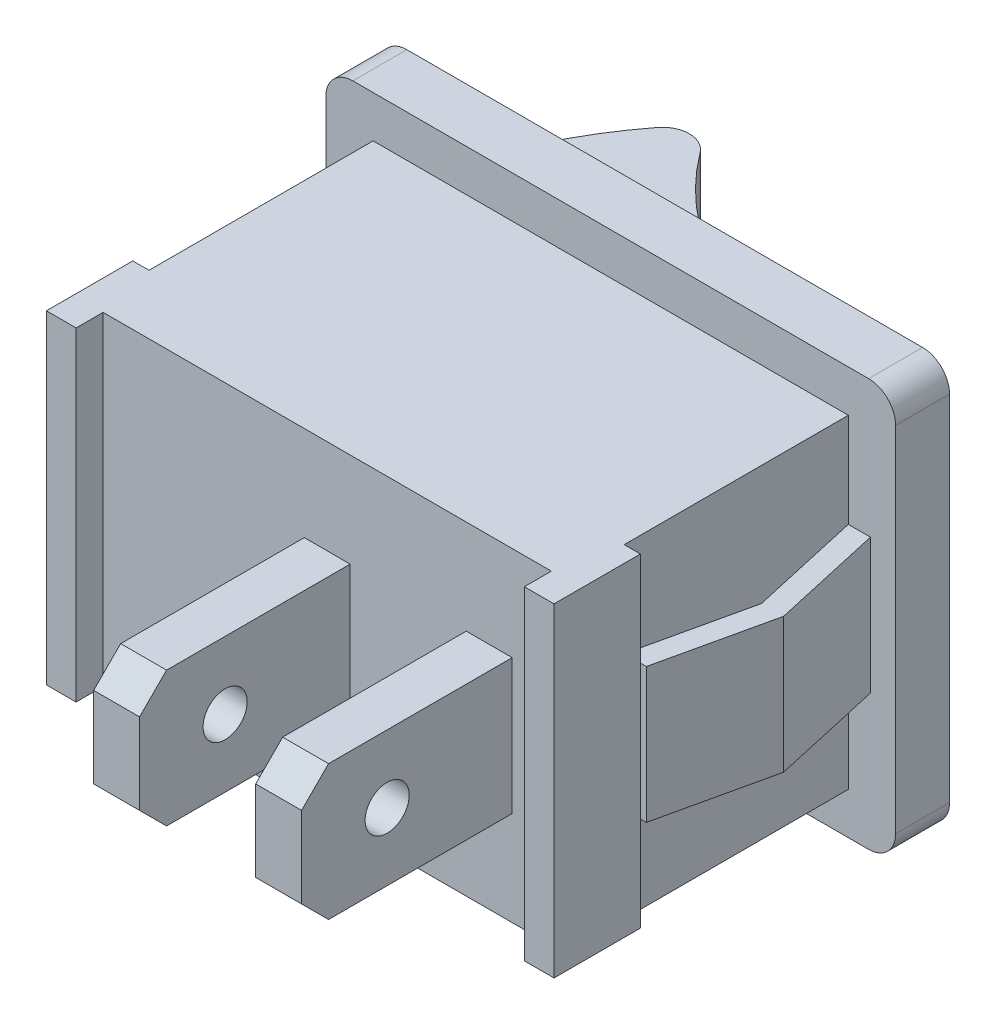
SolidWorks part; units mm, degrees
ref_plane "Front Plane" through (0, 0, 0) normal (0, 0, 1) x (1, 0, 0)
ref_plane "Top Plane" through (0, 0, 0) normal (0, 1, 0) x (1, 0, 0)
ref_plane "Right Plane" through (0, 0, 0) normal (1, 0, 0) x (0, 0, -1)
sketch "Sketch1" plane through (0, 0, 0) normal (0, 1, 0) x (1, 0, 0)
  line L0 (-55, 0) -> (55, 0) construction
  line L1 (-8.3, 0) -> (8.3, 0)
  line L2 (-8.8, 2.2) -> (-8.8, 10.5)
  line L3 (-8.8, 10.5) -> (8.8, 10.5)
  line L4 (8.8, 2.2) -> (8.8, 10.5)
  line L6 (0, -55) -> (0, 55) construction
  line L7 (8.3, -1) -> (8.3, 0)
  line L8 (8.8, 2.2) -> (9.4, 2.2)
  line L9 (-9.4, 2.2) -> (-9.4, -1)
  line L10 (8.3, -1) -> (9.4, -1)
  line L11 (9.4, 2.2) -> (9.4, -1)
  line L12 (-8.3, -1) -> (-9.4, -1)
  line L13 (-8.3, -1) -> (-8.3, 0)
  line L14 (-8.8, 2.2) -> (-9.4, 2.2)
  dimension "D1" = 17.6
  dimension "D2" = 8.3
  dimension "D3" = 9.4
  dimension "D4" = 8.3
  dimension "D5" = 10.5
  dimension "D6" = 1
extrude "Boss-Extrude1" add sketch "Sketch1" along normal mid plane 12
sketch "Sketch2" plane through (0, 0, -10.5) normal (0, 0, -1) x (-1, 0, 0)
  line L0 (8.8, 6) -> (8.8, -6) construction
  line L1 (-10.55, 7.55) -> (10.55, 7.55)
  line L2 (-10.55, 7.55) -> (-10.55, -7.55)
  line L3 (-10.55, -7.55) -> (10.55, -7.55)
  line L4 (10.55, 7.55) -> (10.55, -7.55)
  line L5 (8.8, 6) -> (8.8, -6) construction
  line L6 (8.8, 0) -> (-10.55, 0) construction
  line L7 (0, 0) -> (0, 7.55) construction
  line L8 (0, 55) -> (0, -55) construction
  dimension "D1" = 21.1
  dimension "D2" = 15.1
extrude "Boss-Extrude2" add sketch "Sketch2" along normal blind 2
fillet "Fillet1" radius 1 4 edges at (-10.55, 7.55, -11.5) (-10.55, -7.55, -11.5) (10.55, -7.55, -11.5) (10.55, 7.55, -11.5)
sketch "Sketch3" plane through (0, 0, 0) normal (1, 0, 0) x (0, 0, -1)
  line L0 (0, 8.305) -> (0, -8.305) construction
  line L1 (0, 2.5) -> (-6.8, 2.5)
  line L2 (0, 2.5) -> (0, -2.5)
  line L3 (0, -2.5) -> (-6.8, -2.5)
  line L4 (-7.8, 1.5) -> (-7.8, -1.5)
  line L5 (10.5, 0) -> (0, 0) construction
  line L6 (10.5, 6) -> (10.5, -6) construction
  line L7 (-6.8, 2.5) -> (-7.8, 1.5)
  line L8 (-6.8, -2.5) -> (-7.8, -1.5)
  line L9 (7.425, 0) -> (-7.425, 0) construction
  circle A0 centre (-4.631, 0) radius 0.817
  point P1 (-7.8, -2.5)
  point P3 (-7.8, 2.5)
  dimension "D1" = 5
  dimension "D2" = 7.8
extrude "Boss-Extrude3" add sketch "Sketch3" along normal mid plane 1.7
pattern_linear "LPattern1" count 2 spacing 6 along (1, 0, 0) of "Boss-Extrude3"
sketch "Sketch4" plane through (0, 0, 0) normal (0, 1, 0) x (1, 0, 0)
  line L0 (7.177, 12.8006) -> (7.177, 12.5)
  line L1 (-9.55, 12.5) -> (9.55, 12.5) construction
  line L2 (-7.7109, 12.5) -> (7.177, 12.5)
  arc A0 (-3.622, 17.4321) -> (7.177, 12.8006) centre (5.7794, 24.4473) ccw
  arc A1 (-5.214, 17.4466) -> (-7.7109, 12.5) centre (6.2774, 8.5425) ccw
  arc A2 (-3.622, 17.4321) -> (-5.214, 17.4466) centre (-4.4235, 16.8341) ccw
  dimension "D1" = 1
extrude "Boss-Extrude4" add sketch "Sketch4" along normal mid plane 9.5
sketch "Sketch5" plane through (0, 0, 0) normal (0, 1, 0) x (1, 0, 0)
  line L0 (8.8, 10.5) -> (9.7302, 6.35)
  line L1 (9.7302, 6.35) -> (8.8, 2.2)
  line L2 (9.6198, 10.5) -> (10.55, 6.35)
  line L3 (10.55, 6.35) -> (9.6198, 2.2)
  line L4 (10.55, 12.5) -> (10.55, 10.5) construction
  line L5 (8.8, 10.5) -> (9.6198, 10.5)
  line L6 (8.8, 2.2) -> (9.6198, 2.2)
  line L7 (10.55, 6.35) -> (9.5806, 2.025) construction
  line L8 (9.5806, 10.675) -> (10.55, 6.35) construction
  dimension "D1" = 0.8
extrude "Boss-Extrude5" add sketch "Sketch5" along normal mid plane 5
mirror "Mirror1" about plane through (0, 0, 0) normal (1, 0, 0) of "Boss-Extrude5"
